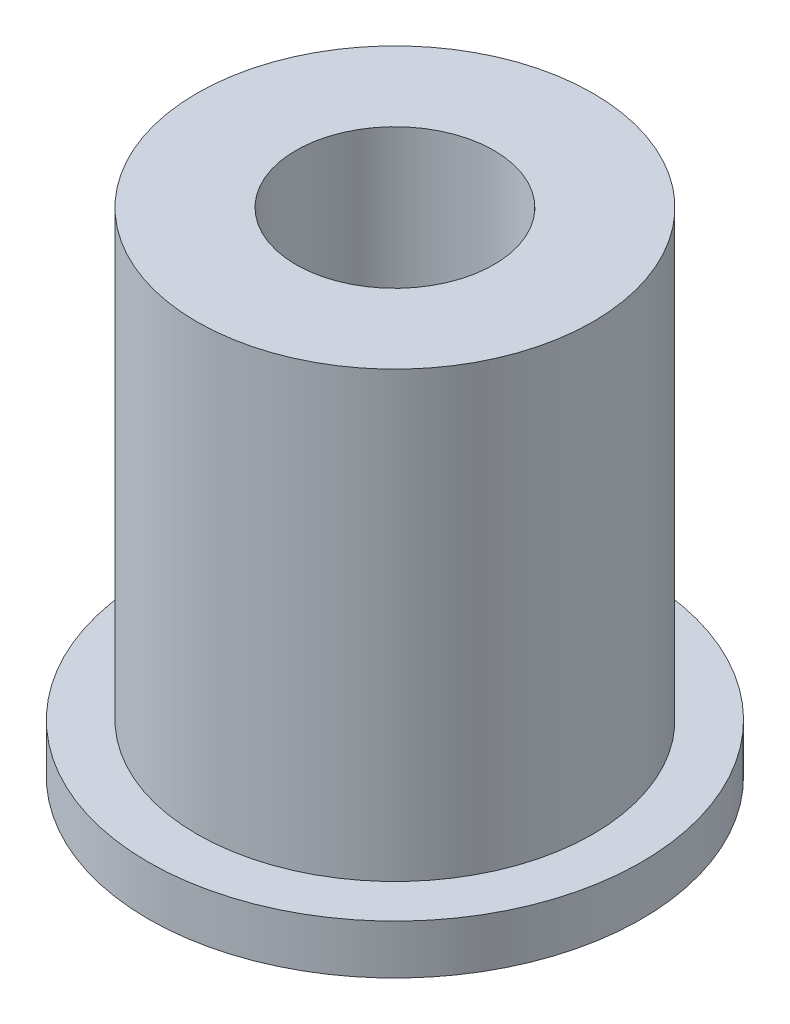
SolidWorks part; units mm, degrees
ref_plane "Front" through (0, 0, 0) normal (0, 0, 1) x (1, 0, 0)
ref_plane "Top" through (0, 0, 0) normal (0, 1, 0) x (1, 0, 0)
ref_plane "Right" through (0, 0, 0) normal (1, 0, 0) x (0, 0, -1)
sketch "Sketch1" plane through (0, 0, 0) normal (0, 1, 0) x (1, 0, 0)
  circle A0 centre (0, 0) radius 3.1877
  circle A1 centre (0, 0) radius 6.3754
  circle A2 centre (0, 0) radius 7.9375
  dimension "ID" = 6.3754
  dimension "OD" = 12.7508
  dimension "FlangeOD" = 15.875
sketch "Sketch2" plane through (0, 0, 0) normal (0, 1, 0) x (1, 0, 0)
  circle A0 centre (0, 0) radius 3.1877 construction
  circle A1 centre (0, 0) radius 6.3754 construction
  circle A2 centre (0, 0) radius 3.1877
  circle A3 centre (0, 0) radius 6.3754
extrude "Boss-Extrude1" add sketch "Sketch2" along normal blind 15.875
sketch "Sketch3" plane through (0, 0, 0) normal (0, 1, 0) x (1, 0, 0)
  circle A0 centre (0, 0) radius 7.9375 construction
  circle A1 centre (0, 0) radius 6.3754 construction
  circle A2 centre (0, 0) radius 7.9375
  circle A3 centre (0, 0) radius 6.3754
extrude "Boss-Extrude2" add sketch "Sketch3" along normal blind 1.5875
